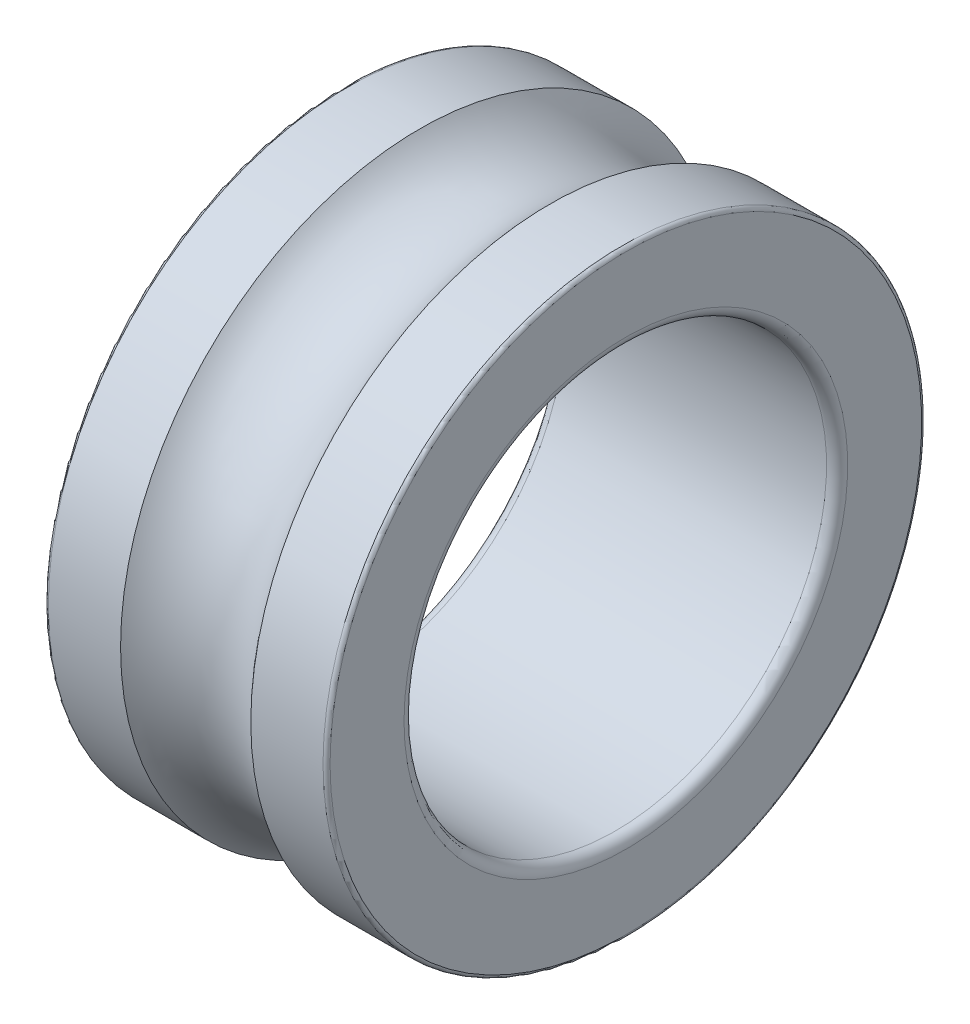
SolidWorks part; units mm, degrees
ref_plane "Plan de face" through (0, 0, 0) normal (0, 0, 1) x (1, 0, 0)
ref_plane "Plan de dessus" through (0, 0, 0) normal (0, 1, 0) x (1, 0, 0)
ref_plane "Plan de droite" through (0, 0, 0) normal (1, 0, 0) x (0, 0, -1)
ref_plane "Plan1" through (0, 0, 0) normal (0, 0, 1) x (1, 0, 0)
sketch "Esquisse1" plane through (0, 0, 0) normal (0, 0, 1) x (1, 0, 0)
  line L0 (0.3, 6) -> (7.7, 6)
  line L1 (8, 6.3) -> (8, 8.4)
  line L2 (7.9, 8.5) -> (5.8491, 8.5)
  line L3 (2.1509, 8.5) -> (0.1, 8.5)
  line L4 (0, 8.4) -> (0, 6.3)
  line L5 (100, 0) -> (-100, 0) construction
  arc A0 (0, 6.3) -> (0.3, 6) centre (0.3, 6.3) ccw
  arc A1 (7.7, 6) -> (8, 6.3) centre (7.7, 6.3) ccw
  arc A2 (8, 8.4) -> (7.9, 8.5) centre (7.9, 8.4) ccw
  arc A3 (5.8491, 8.5) -> (2.1509, 8.5) centre (4, 10) cw
  arc A4 (0.1, 8.5) -> (0, 8.4) centre (0.1, 8.4) ccw
revolve "Révolution1" add sketch "Esquisse1" angle 360 about L5
